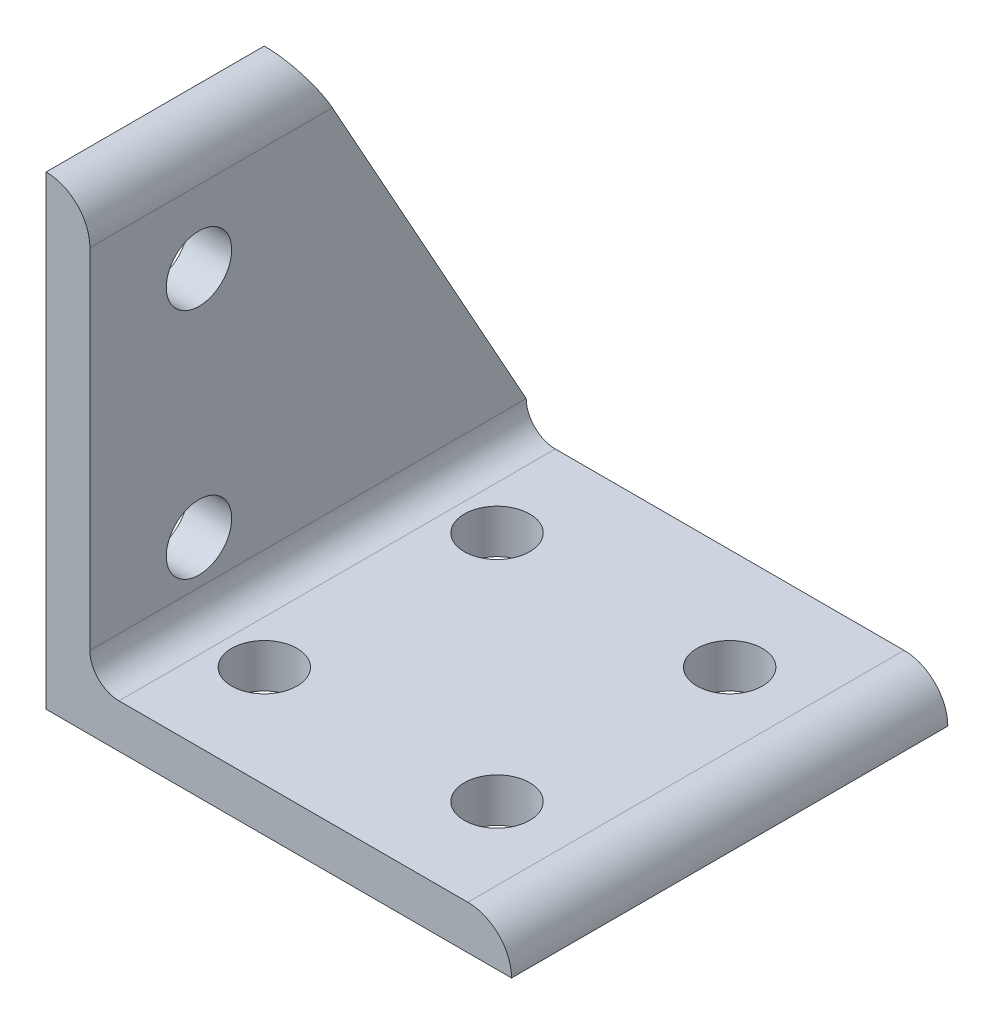
SolidWorks part; units mm, degrees
ref_plane "Front Plane" through (0, 0, 0) normal (0, 0, 1) x (1, 0, 0)
ref_plane "Top Plane" through (0, 0, 0) normal (0, 1, 0) x (1, 0, 0)
ref_plane "Right Plane" through (0, 0, 0) normal (1, 0, 0) x (0, 0, -1)
sketch "Sketch1" plane through (0, 0, 0) normal (0, 0, 1) x (1, 0, 0)
  line L0 (25.4, -25.4) -> (-25.4, -25.4) construction
  line L1 (-25.4, 25.4) -> (-25.4, -25.4) construction
  line L2 (25.4, -25.4) -> (25.4, -20.6248) construction
  point P3 (0, -25.4)
  point P6 (-25.4, 0)
  dimension "Length" = 50.8
  dimension "Thickness" = 4.7752
sketch "Sketch2" plane through (0, 0, 0) normal (1, 0, 0) x (0, 0, -1)
  line L0 (23.8125, 0) -> (-23.8125, 0) construction
  line L1 (0, 25.4) -> (-23.8125, 25.4) construction
  line L2 (-11.9062, 25.4) -> (-11.9063, 12.7) construction
  line L3 (-15.475, 12.7) -> (-8.3376, 12.7) construction
  point P10 (0, 0)
  point P13 (0, 25.4)
  point P19 (-11.9063, 12.7)
  dimension "Width" = 47.625
  dimension "Hole Dia" = 7.1374
  dimension "Hole Spacing" = 25.4
sketch "Sketch3" plane through (0, 0, 0) normal (0, 1, 0) x (1, 0, 0)
  line L1 (25.4, 0) -> (-25.4, 0) construction
  line L2 (25.4, 0) -> (-25.4, 0) construction
  point P0 (-12.7, 12.7)
  dimension "Hole to Edge" = 12.7
  dimension "D1" = 25.4
sketch "Sketch4" plane through (0, 0, 0) normal (0, 0, 1) x (1, 0, 0)
  line L0 (-25.4, 25.4) -> (-25.4, -25.4)
  line L1 (-25.4, -25.4) -> (25.4, -25.4)
  line L2 (-20.6248, 20.6248) -> (-20.6248, -17.4498)
  line L3 (-17.4498, -20.6248) -> (20.6248, -20.6248)
  arc A0 (-20.6248, -17.4498) -> (-17.4498, -20.6248) centre (-17.4498, -17.4498) ccw
  arc A1 (20.6248, -20.6248) -> (25.4, -25.4) centre (20.6248, -25.4) cw
  arc A2 (-20.6248, 20.6248) -> (-25.4, 25.4) centre (-25.4, 20.6248) ccw
  dimension "Radius" = 3.175
extrude "Boss-Extrude1" add sketch "Sketch4" against normal up to vertex (23.8125 mm away) and the other way up to vertex (23.8125 mm away) up to point (0, 0, -23.8125) other way up to point (0, 0, 23.8125)
sketch "Sketch5" plane through (-20.6248, 0, 0) normal (1, 0, 0) x (0, 0, -1)
  line L1 (23.8125, 25.4) -> (-23.8125, 25.4) construction
  line L3 (0, 25.4) -> (0, -25.4) construction
  line L4 (0, 25.4) -> (0, -25.4) construction
  line L11 (23.8125, 25.4) -> (0, 25.4)
  line L12 (23.8125, -17.4498) -> (23.8125, 25.4)
  line L13 (23.8125, -17.4498) -> (0, 25.4)
extrude "Cut-Extrude1" cut sketch "Sketch5" against normal through all both and the other way through all
sketch "Sketch6" plane through (-20.6248, 0, 0) normal (1, 0, 0) x (0, 0, -1)
  line L0 (-15.475, 12.7) -> (-8.3376, 12.7) construction
  line L1 (23.8125, 0) -> (-23.8125, 0) construction
  line L2 (23.8125, 0) -> (-23.8125, 0) construction
  circle A0 centre (-11.9063, 12.7) radius 3.5687
  circle A1 centre (-11.9062, -12.7) radius 3.5687
extrude "Cut-Extrude2" cut sketch "Sketch6" against normal through all
sketch "Sketch7" plane through (0, -20.6248, 0) normal (0, 1, 0) x (1, 0, 0)
  line L0 (25.4, 0) -> (-25.4, 0) construction
  line L1 (25.4, 0) -> (-25.4, 0) construction
  circle A0 centre (-12.7, 12.7) radius 3.5687
  circle A1 centre (12.7, 12.7) radius 3.5687
  circle A2 centre (12.7, -12.7) radius 3.5687
  circle A3 centre (-12.7, -12.7) radius 3.5687
  dimension "D1" = 7.1374
  dimension "D2" = 25.4
extrude "Cut-Extrude3" cut sketch "Sketch7" against normal through all
equation "\"D1@Sketch3\" = \"Hole Spacing@Sketch2\""
equation "\"D1@Sketch7\"=\"Hole Dia@Sketch2\""
equation "\"D2@Sketch7\"=\"Hole Spacing@Sketch2\""
